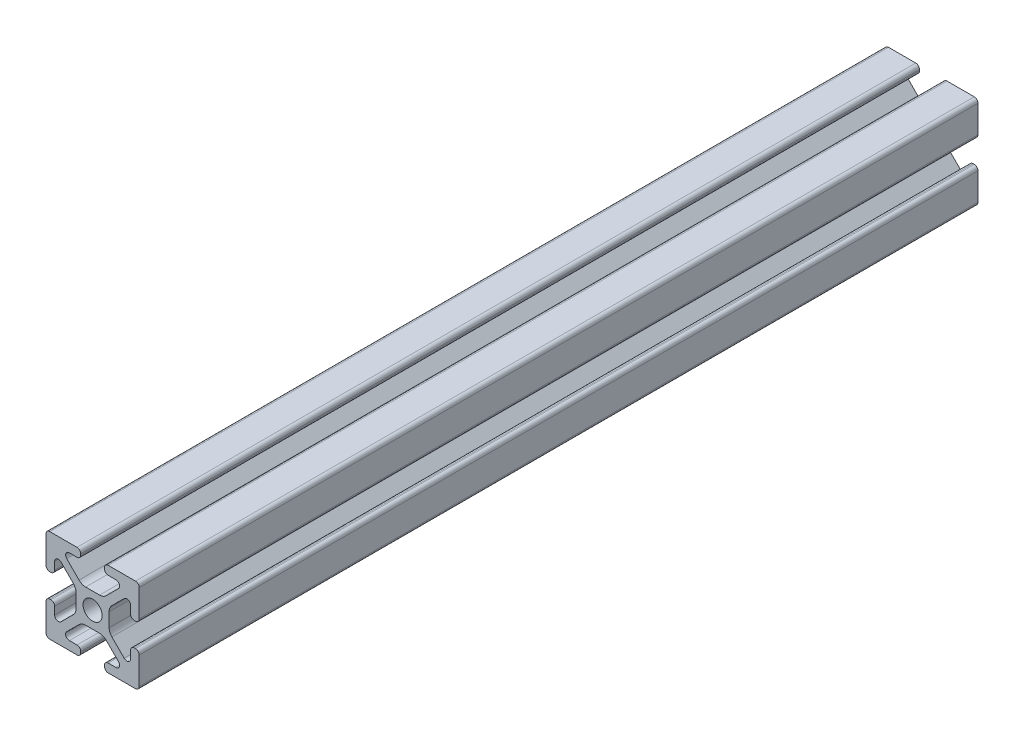
SolidWorks part; units mm, degrees
ref_plane "Front" through (0, 0, 0) normal (0, 0, 1) x (1, 0, 0)
ref_plane "Top" through (0, 0, 0) normal (0, 1, 0) x (1, 0, 0)
ref_plane "Right" through (0, 0, 0) normal (1, 0, 0) x (0, 0, -1)
sketch "Sketch1" plane through (0, 0, 0) normal (0, 0, 1) x (1, 0, 0)
  line L0 (0, 0) -> (25.4, 0) construction
  line L1 (25.4, 0) -> (25.4, 25.4) construction
  line L2 (25.4, 25.4) -> (0, 25.4) construction
  line L3 (0, 25.4) -> (0, 0) construction
  line L4 (12.7, 0) -> (12.7, 12.7) construction
  line L5 (12.7, 0) -> (15.9385, 0) construction
  line L6 (15.9385, 0) -> (15.9385, 25.4) construction
  line L7 (15.9385, 25.4) -> (9.4615, 25.4) construction
  line L8 (9.4615, 25.4) -> (9.4615, 0) construction
  line L9 (25.4, 25.4) -> (0, 0) construction
  line L10 (24.6187, 26.1813) -> (-0.7813, 0.7813)
  line L11 (26.1813, 24.6187) -> (0.7813, -0.7813)
  line L12 (0, 25.4) -> (25.4, 0) construction
  line L13 (-0.7813, 24.6187) -> (24.6187, -0.7813)
  line L14 (0.7813, 26.1813) -> (26.1813, 0.7813)
  line L15 (9.4615, 25.4) -> (0, 25.4) construction
  line L16 (15.9385, 25.4) -> (25.4, 25.4) construction
  line L17 (12.7, 12.7) -> (12.7, 17.2085) construction
  line L18 (12.7, 17.2085) -> (17.2085, 17.2085) construction
  line L19 (17.2085, 17.2085) -> (17.2085, 8.1915) construction
  line L20 (17.2085, 8.1915) -> (8.1915, 8.1915) construction
  line L21 (8.1915, 8.1915) -> (8.1915, 17.2085) construction
  line L22 (8.1915, 17.2085) -> (12.7, 17.2085) construction
  line L23 (8.1915, 8.1915) -> (2.3495, 8.1915) construction
  line L24 (2.3495, 8.1915) -> (2.3495, 0) construction
  line L25 (2.3495, 8.1915) -> (2.3495, 25.4) construction
  line L26 (17.2085, 8.1915) -> (23.0505, 8.1915) construction
  line L27 (23.0505, 8.1915) -> (23.0505, 25.4) construction
  line L28 (23.0505, 8.1915) -> (23.0505, 0) construction
  line L29 (17.2085, 8.1915) -> (17.2085, 2.3495) construction
  line L30 (17.2085, 2.3495) -> (25.4, 2.3495) construction
  line L31 (17.2085, 2.3495) -> (0, 2.3495) construction
  line L32 (17.2085, 17.2085) -> (17.2085, 23.0505) construction
  line L33 (17.2085, 23.0505) -> (25.4, 23.0505) construction
  line L34 (17.2085, 23.0505) -> (0, 23.0505) construction
  line L35 (12.7, 12.7) -> (12.7, 9.4615) construction
  line L36 (12.7, 9.4615) -> (25.4, 9.4615) construction
  line L37 (25.4, 9.4615) -> (25.4, 15.9385) construction
  line L38 (25.4, 15.9385) -> (0, 15.9385) construction
  line L39 (12.7, 9.4615) -> (0, 9.4615) construction
  line L40 (9.4615, 25.4) -> (0, 25.4)
  line L41 (15.9385, 25.4) -> (25.4, 25.4)
  line L42 (25.4, 25.4) -> (25.4, 15.9385)
  line L43 (25.4, 15.9385) -> (25.4, 25.4)
  line L44 (25.4, 9.4615) -> (25.4, 0)
  line L45 (25.4, 0) -> (15.9385, 0)
  line L46 (9.4615, 0) -> (0, 0)
  line L47 (0, 0) -> (0, 9.4615)
  line L48 (0, 15.9385) -> (0, 25.4)
  line L49 (2.3495, 9.4615) -> (2.3495, 3.9121)
  line L50 (3.9121, 2.3495) -> (9.4615, 2.3495)
  line L51 (15.9385, 2.3495) -> (21.4879, 2.3495)
  line L52 (23.0505, 3.9121) -> (23.0505, 9.4615)
  line L53 (23.0505, 9.4615) -> (25.4, 9.4615)
  line L54 (25.4, 15.9385) -> (23.0505, 15.9385)
  line L55 (23.0505, 15.9385) -> (23.0505, 21.4879)
  line L56 (21.4879, 23.0505) -> (15.9385, 23.0505)
  line L57 (15.9385, 23.0505) -> (15.9385, 25.4)
  line L58 (9.4615, 25.4) -> (9.4615, 23.0505)
  line L59 (9.4615, 23.0505) -> (3.9121, 23.0505)
  line L60 (2.3495, 21.4879) -> (2.3495, 15.9385)
  line L61 (2.3495, 15.9385) -> (0, 15.9385)
  line L62 (0, 9.4615) -> (2.3495, 9.4615)
  line L63 (9.4615, 2.3495) -> (9.4615, 0)
  line L64 (15.9385, 2.3495) -> (15.9385, 0)
  line L65 (8.1915, 15.6459) -> (8.1915, 9.7541)
  line L66 (9.7541, 8.1915) -> (15.6459, 8.1915)
  line L67 (17.2085, 9.7541) -> (17.2085, 15.6459)
  line L68 (15.6459, 17.2085) -> (9.7541, 17.2085)
  circle A0 centre (12.7, 12.7) radius 2.6035
  dimension "D1" = 1.1049
  dimension "D2" = 1.1049
  dimension "D3" = 1.1049
  dimension "D4" = 1.1049
extrude "Boss-Extrude1" add sketch "Sketch1" along normal blind 228.6 contours L59 L58 L40 L14 | A0 L14 L40 L48 L13 | L61 L60 L13 L48 | A0 L10 L68 L14 | A0 L13 L65 L10 | A0 L10 L47 L46 L11 | A0 L11 L66 L13 | A0 L13 L45 L44 L14 | A0 L14 L67 L11 | A0 L11 L42 L41 L10 | L57 L56 L10 L41 | L55 L54 L42 L11 | L53 L52 L14 L44 | L51 L64 L45 L13 | L63 L50 L11 L46 | L62 L47 L10 L49
fillet "Fillet1" radius 2.54 8 edges at (8.1915, 9.7541, 114.3) (8.1915, 15.6459, 114.3) (9.7541, 8.1915, 114.3) (15.6459, 8.1915, 114.3) (17.2085, 9.7541, 114.3) (17.2085, 15.6459, 114.3) (15.6459, 17.2085, 114.3) (9.7541, 17.2085, 114.3)
fillet "Fillet2" radius 1.016 20 edges at (25.4, 15.9385, 114.3) (25.4, 0, 114.3) (9.4615, 0, 114.3) (2.3495, 15.9385, 114.3) (25.4, 25.4, 114.3) (15.9385, 25.4, 114.3) (15.9385, 23.0505, 114.3) (23.0505, 15.9385, 114.3) (25.4, 9.4615, 114.3) (23.0505, 9.4615, 114.3) (15.9385, 2.3495, 114.3) (15.9385, 0, 114.3) (0, 0, 114.3) (9.4615, 2.3495, 114.3) (2.3495, 9.4615, 114.3) (0, 9.4615, 114.3) (0, 15.9385, 114.3) (0, 25.4, 114.3) (9.4615, 23.0505, 114.3) (9.4615, 25.4, 114.3)
fillet "Fillet3" radius 1.016 8 edges at (2.3495, 3.9121, 114.3) (3.9121, 2.3495, 114.3) (23.0505, 3.9121, 114.3) (21.4879, 2.3495, 114.3) (23.0505, 21.4879, 114.3) (21.4879, 23.0505, 114.3) (2.3495, 21.4879, 114.3) (3.9121, 23.0505, 114.3)
